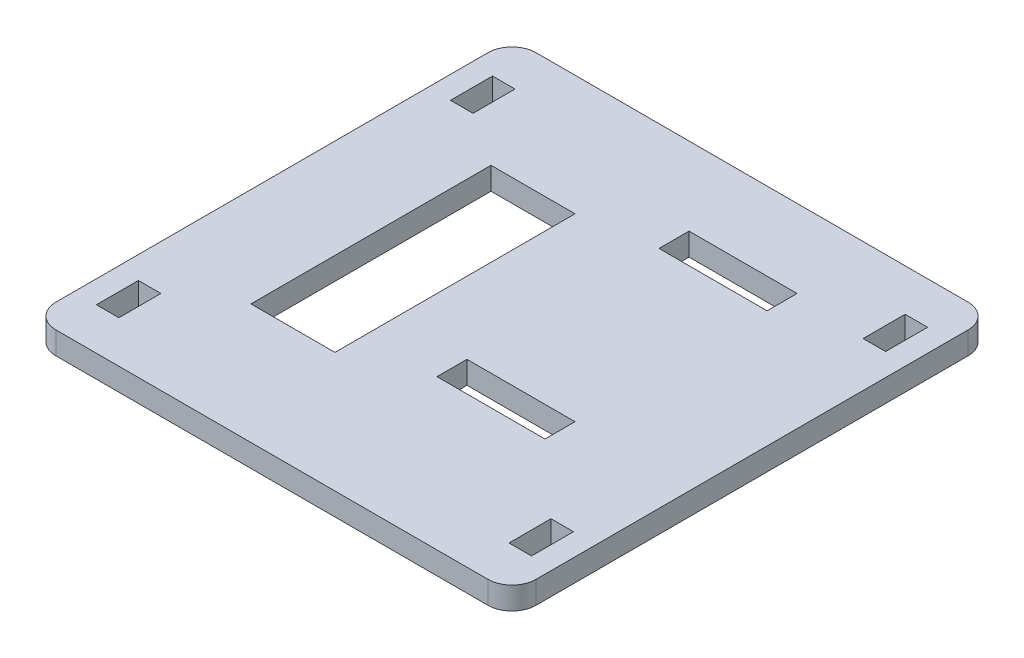
SolidWorks part; units mm, degrees
ref_plane "Front Plane" through (0, 0, 0) normal (0, 0, 1) x (1, 0, 0)
ref_plane "Top Plane" through (0, 0, 0) normal (0, 1, 0) x (1, 0, 0)
ref_plane "Right Plane" through (0, 0, 0) normal (1, 0, 0) x (0, 0, -1)
sketch "Sketch1" plane through (0, 0, 0) normal (0, 1, 0) x (1, 0, 0)
  line L0 (-50.8, 101.6) -> (-50.8, 69.1254) construction
  line L1 (0, 0) -> (-101.6, 0)
  line L2 (0, 0) -> (0, 101.6)
  line L3 (0, 101.6) -> (-101.6, 101.6)
  line L4 (-101.6, 0) -> (-101.6, 101.6)
  line L5 (-101.6, 50.8) -> (-93.8482, 50.8) construction
  line L6 (-96.8375, 17.78) -> (-92.075, 17.78)
  line L7 (-96.8375, 92.71) -> (-92.075, 92.71)
  line L8 (-96.8375, 92.71) -> (-96.8375, 83.82)
  line L9 (-96.8375, 83.82) -> (-92.075, 83.82)
  line L10 (-92.075, 92.71) -> (-92.075, 83.82)
  line L11 (-80.645, 76.2) -> (-62.865, 76.2)
  line L12 (-80.645, 76.2) -> (-80.645, 25.4)
  line L13 (-80.645, 25.4) -> (-62.865, 25.4)
  line L14 (-62.865, 76.2) -> (-62.865, 25.4)
  line L15 (-47.625, 85.09) -> (-24.765, 85.09)
  line L16 (-47.625, 85.09) -> (-47.625, 78.74)
  line L17 (-47.625, 78.74) -> (-24.765, 78.74)
  line L18 (-24.765, 85.09) -> (-24.765, 78.74)
  line L19 (-92.075, 8.89) -> (-92.075, 17.78)
  line L20 (-96.8375, 8.89) -> (-92.075, 8.89)
  line L21 (-96.8375, 8.89) -> (-96.8375, 17.78)
  line L22 (-4.7625, 8.89) -> (-4.7625, 17.78)
  line L23 (-4.7625, 8.89) -> (-9.525, 8.89)
  line L24 (-9.525, 8.89) -> (-9.525, 17.78)
  line L25 (-4.7625, 17.78) -> (-9.525, 17.78)
  line L26 (-4.7625, 83.82) -> (-9.525, 83.82)
  line L27 (-9.525, 92.71) -> (-9.525, 83.82)
  line L28 (-4.7625, 92.71) -> (-9.525, 92.71)
  line L29 (-4.7625, 92.71) -> (-4.7625, 83.82)
  line L30 (-47.625, 38.1) -> (-24.765, 38.1)
  line L31 (-24.765, 31.75) -> (-24.765, 38.1)
  line L32 (-47.625, 31.75) -> (-24.765, 31.75)
  line L33 (-47.625, 31.75) -> (-47.625, 38.1)
  point P17 (-92.075, 88.265)
  dimension "D1" = 101.6
  dimension "D2" = 101.6
  dimension "D3" = 4.7625
  dimension "D4" = 8.89
  dimension "D5" = 8.89
  dimension "D6" = 4.7625
  dimension "D7" = 17.78
  dimension "D8" = 50.8
  dimension "D9" = 25.4
  dimension "D10" = 11.43
  dimension "D11" = 24.765
  dimension "D12" = 6.35
  dimension "D13" = 22.86
  dimension "D14" = 16.51
  dimension "D15" = 6.35
  dimension "D17" = 40.64
extrude "Boss-Extrude1" add sketch "Sketch1" along normal blind 4.7625
fillet "Fillet1" radius 5.08 4 edges at (-101.6, 2.3813, 0) (0, 2.3813, 0) (0, 2.3813, -101.6) (-101.6, 2.3813, -101.6)
